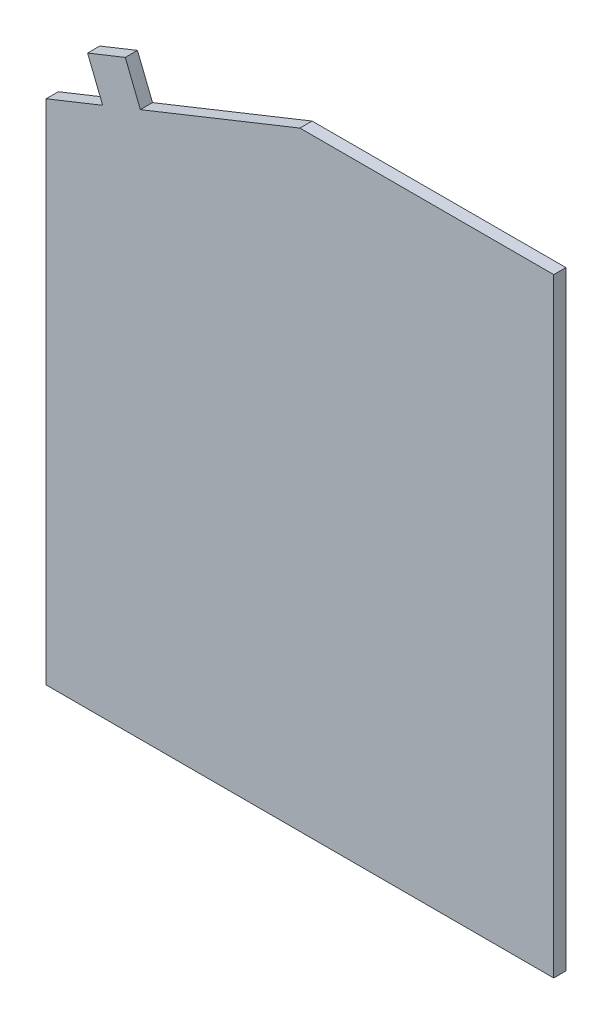
SolidWorks part; units mm, degrees
ref_plane "Plan de face" through (0, 0, 0) normal (0, 0, 1) x (1, 0, 0)
ref_plane "Plan de dessus" through (0, 0, 0) normal (0, 1, 0) x (1, 0, 0)
ref_plane "Plan de droite" through (0, 0, 0) normal (1, 0, 0) x (0, 0, -1)
sketch "Esquisse1" plane through (0, 0, 0) normal (0, 0, 1) x (1, 0, 0)
  line L0 (0, 0) -> (125, 0)
  line L1 (0, 0) -> (0, 125)
  line L2 (0, 125) -> (125, 175) construction
  line L4 (125, 175) -> (125, 0) construction
  line L5 (23.2119, 134.2848) -> (13.9272, 130.5709) construction
  line L6 (23.2119, 134.2848) -> (19.498, 143.5695)
  line L7 (13.9272, 130.5709) -> (10.2132, 139.8556)
  line L8 (19.498, 143.5695) -> (10.2132, 139.8556)
  line L9 (0, 125) -> (13.9272, 130.5709)
  line L10 (23.2119, 134.2848) -> (125, 175) construction
  line L11 (125, 150) -> (62.5, 150)
  line L12 (23.2119, 134.2848) -> (62.5, 150)
  line L13 (125, 150) -> (125, 0)
  dimension "D1" = 125
  dimension "D2" = 175
  dimension "D3" = 125
  dimension "D4" = 10
  dimension "D5" = 10
  dimension "D6" = 15
  dimension "D7" = 25
extrude "Boss.-Extru.1" add sketch "Esquisse1" along normal blind 3
